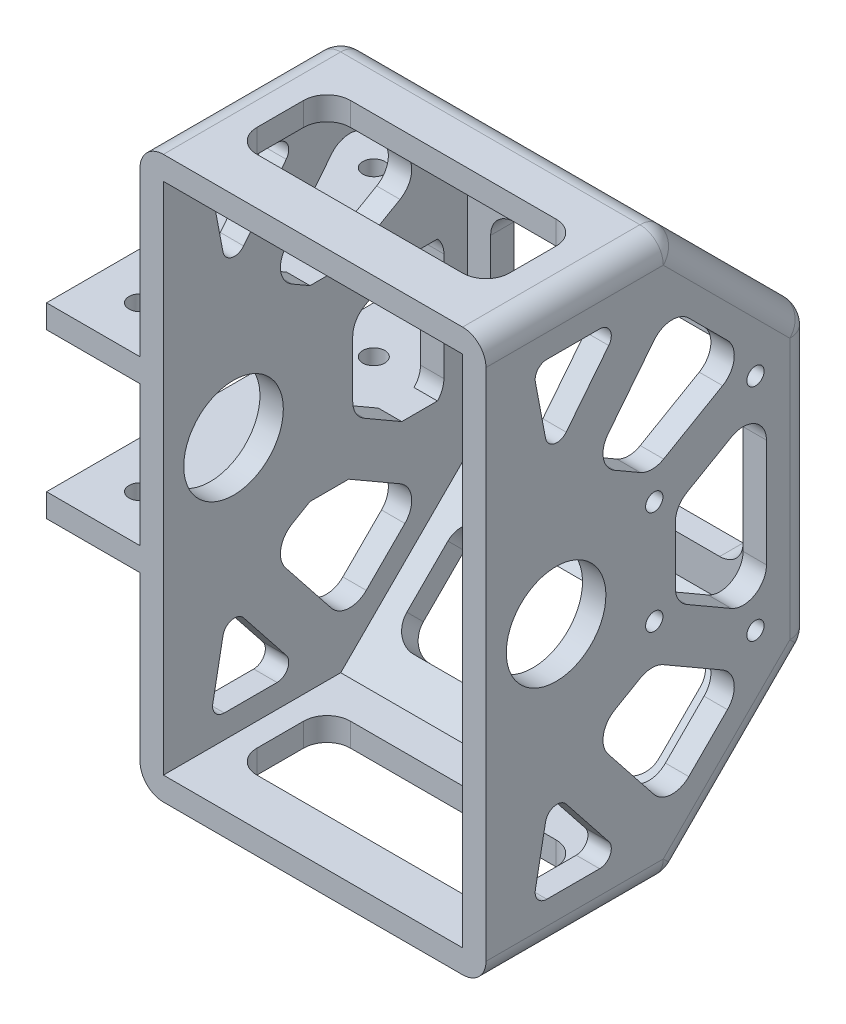
SolidWorks part; units mm, degrees
ref_plane "正面" through (0, 0, 0) normal (0, 0, 1) x (1, 0, 0)
ref_plane "平面" through (0, 0, 0) normal (0, 1, 0) x (1, 0, 0)
ref_plane "右側面" through (0, 0, 0) normal (1, 0, 0) x (0, 0, -1)
sketch "ｽｹｯﾁ1" plane through (0, 0, 0) normal (0, 0, 1) x (1, 0, 0)
  line L1 (-37, 60) -> (37, 60)
  line L2 (-37, 60) -> (-37, -60)
  line L3 (-37, -60) -> (37, -60)
  line L4 (37, 60) -> (37, -60)
  line L5 (-37, 60) -> (37, -60) construction
  line L6 (-37, -60) -> (37, 60) construction
  point P0 (0, 0)
  dimension "D1" = 120
  dimension "D2" = 74
extrude "ﾎﾞｽ - 押し出し1" add sketch "ｽｹｯﾁ1" along normal blind 70
chamfer "面取り2" distance 30 angle 45 2 edges at (0, 60, 0) (0, -60, 0)
sketch "ｽｹｯﾁ2" plane through (-37, 0, 0) normal (-1, 0, 0) x (0, 0, 1)
  line L0 (70, 60) -> (70, -60) construction
  line L1 (55, -23.6714) -> (55, -60)
  line L2 (55, 23.6714) -> (34.5, 11.8357)
  line L3 (34.5, 11.8357) -> (34.5, -11.8357)
  line L4 (34.5, -11.8357) -> (55, -23.6714)
  line L5 (55, -23.6714) -> (75.5, -11.8357)
  line L6 (75.5, -11.8357) -> (75.5, 11.8357)
  line L7 (75.5, 11.8357) -> (55, 23.6714)
  line L8 (70, -60) -> (30, -60) construction
  line L9 (34.5, -11.8357) -> (1.1122, -31.1122)
  line L10 (55, -23.6714) -> (34.1421, -50)
  line L11 (0, -30) -> (30, -60) construction
  line L12 (51.0808, -20.5665) -> (30.2229, -46.8952)
  line L14 (34.5, 11.8357) -> (1.1122, 31.1122)
  line L15 (30, 60) -> (0, 30) construction
  line L16 (32, -16.1658) -> (52.5, -28.0015)
  line L17 (32, -7.5056) -> (-1.3878, -26.782)
  line L18 (57.5, -28.0015) -> (80.5, -14.7224)
  line L19 (80.5, -14.7224) -> (80.5, 14.7224)
  line L20 (80.5, 14.7224) -> (57.5, 28.0015)
  line L21 (29.5, 11.8357) -> (29.5, -11.8357)
  line L22 (37, 16.1658) -> (3.6122, 35.4423)
  line L23 (52.5, 28.0015) -> (32, 16.1658)
  line L24 (55, 23.6714) -> (34.1421, 50)
  line L25 (58.9192, 26.7762) -> (38.0613, 53.1048)
  line L26 (37, -7.5056) -> (57.5, -19.3412)
  line L27 (37, -16.1658) -> (3.6122, -35.4423)
  line L28 (52.5, -19.3412) -> (70.5, -8.9489)
  line L29 (70.5, -8.9489) -> (70.5, 8.9489)
  line L30 (70.5, 8.9489) -> (52.5, 19.3412)
  line L31 (39.5, 11.8357) -> (39.5, -11.8357)
  line L32 (32, 7.5056) -> (-1.3878, 26.782)
  line L33 (57.5, 19.3412) -> (37, 7.5056)
  line L34 (58.9192, -26.7762) -> (38.0613, -53.1048)
  line L35 (51.0808, 20.5665) -> (30.2229, 46.8952)
  line L36 (55, 23.6714) -> (60, 50)
  line L37 (55, -23.6714) -> (60, -50)
  line L38 (50.0878, -24.6042) -> (55.0878, -50.9329)
  line L39 (59.9122, 22.7385) -> (64.9122, 49.0671)
  line L40 (59.9122, -22.7385) -> (64.9122, -49.0671)
  line L41 (50.0878, 24.6042) -> (55.0878, 50.9329)
  line L47 (60, 50) -> (34.1421, 50)
  line L48 (34.1421, 50) -> (10, 25.8579)
  line L49 (10, 25.8579) -> (10, -25.8579)
  line L50 (10, -25.8579) -> (34.1421, -50)
  line L51 (34.1421, -50) -> (60, -50)
  line L52 (60, -50) -> (60, 50)
  line L53 (60, 50) -> (34.1421, 50)
  line L54 (34.1421, 50) -> (10, 25.8579)
  line L55 (10, 25.8579) -> (10, -25.8579)
  line L56 (10, -25.8579) -> (34.1421, -50)
  line L57 (34.1421, -50) -> (60, -50)
  line L58 (60, -50) -> (60, 50)
  circle A0 centre (55, 0) radius 10.65
  circle A1 centre (55, 0) radius 20.5 construction
  dimension "D1" = 21.3
  dimension "D2" = 15
  dimension "D3" = 41
  dimension "D4" = 5
  dimension "D5" = 5
  dimension "D6" = 10
  dimension "D7" = 5
  dimension "D8" = 5
  dimension "D9" = 5
  dimension "D10" = 5
shell "ｼｪﾙ1" thickness 5
extrude "ｶｯﾄ - 押し出し1" cut sketch "ｽｹｯﾁ2" against normal through all
sketch "ｽｹｯﾁ3" plane through (0, -15, -15) normal (0, -0.7071, -0.7071) x (1, 0, 0)
  line L8 (-27, 53.6396) -> (-27, 31.2132)
  line L9 (-27, 31.2132) -> (27, 31.2132)
  line L10 (27, 31.2132) -> (27, 53.6396)
  line L11 (27, 53.6396) -> (-27, 53.6396)
  line L12 (-27, 53.6396) -> (-27, 31.2132)
  line L13 (-27, 31.2132) -> (27, 31.2132)
  line L14 (27, 31.2132) -> (27, 53.6396)
  line L15 (27, 53.6396) -> (-27, 53.6396)
  dimension "D1" = 10
extrude "ｶｯﾄ - 押し出し2" cut sketch "ｽｹｯﾁ3" against normal blind 70
sketch "ｽｹｯﾁ4" plane through (0, 15, -15) normal (0, 0.7071, -0.7071) x (1, 0, 0)
  line L8 (27, -53.6396) -> (27, -31.2132)
  line L9 (27, -31.2132) -> (-27, -31.2132)
  line L10 (-27, -31.2132) -> (-27, -53.6396)
  line L11 (-27, -53.6396) -> (27, -53.6396)
  line L12 (27, -53.6396) -> (27, -31.2132)
  line L13 (27, -31.2132) -> (-27, -31.2132)
  line L14 (-27, -31.2132) -> (-27, -53.6396)
  line L15 (-27, -53.6396) -> (27, -53.6396)
  dimension "D1" = 10
extrude "ｶｯﾄ - 押し出し3" cut sketch "ｽｹｯﾁ4" against normal blind 70
sketch "ｽｹｯﾁ5" plane through (0, 0, 0) normal (0, 0, -1) x (-1, 0, 0)
  line L8 (27, -20) -> (27, 20)
  line L9 (27, 20) -> (-27, 20)
  line L10 (-27, 20) -> (-27, -20)
  line L11 (-27, -20) -> (27, -20)
  line L12 (27, -20) -> (27, 20)
  line L13 (27, 20) -> (-27, 20)
  line L14 (-27, 20) -> (-27, -20)
  line L15 (-27, -20) -> (27, -20)
  dimension "D1" = 10
extrude "ｶｯﾄ - 押し出し4" cut sketch "ｽｹｯﾁ5" against normal blind 70
sketch "ｽｹｯﾁ7" plane through (0, 60, 0) normal (0, 1, 0) x (1, 0, 0)
  line L8 (27, -60) -> (27, -40)
  line L9 (27, -40) -> (-27, -40)
  line L10 (-27, -40) -> (-27, -60)
  line L11 (-27, -60) -> (27, -60)
  line L12 (27, -60) -> (27, -40)
  line L13 (27, -40) -> (-27, -40)
  line L14 (-27, -40) -> (-27, -60)
  line L15 (-27, -60) -> (27, -60)
  dimension "D1" = 10
extrude "ｶｯﾄ - 押し出し5" cut sketch "ｽｹｯﾁ7" against normal through all
fillet "ﾌｨﾚｯﾄ1" radius 5 58 edges at (27, 51.1612, 24.6967) (-27, 51.1612, 24.6967) (-27, 35.3033, 8.8388) (27, 35.3033, 8.8388) (-27, 20, 2.5) (-27, -20, 2.5) (27, 20, 2.5) (27, -20, 2.5) (-27, -35.3033, 8.8388) (-27, -51.1612, 24.6967) (27, -51.1612, 24.6967) (27, -35.3033, 8.8388) (34.5, -29.596, 13.7382) (34.5, -17.6092, 34.5) (34.5, 17.6092, 34.5) (34.5, 29.596, 13.7382) (34.5, -20.2073, 10) (34.5, -8.9489, 29.5) (34.5, 8.9489, 29.5) (34.5, 20.2073, 10) (-34.5, 29.596, 13.7382) (-34.5, 17.6092, 34.5) (-34.5, 20.2073, 10) (-34.5, 8.9489, 29.5) (-34.5, -20.2073, 10) (-34.5, -8.9489, 29.5) (-34.5, -29.596, 13.7382) (-34.5, -17.6092, 34.5) (-27, -57.5, 60) (-27, -57.5, 40) (27, -57.5, 40) (27, -57.5, 60) (27, 57.5, 60) (27, 57.5, 40) (-27, 57.5, 40) (-27, 57.5, 60) (37, -45, 15) (37, -60, 50) (-37, -60, 50) (-37, -45, 15) (0, -30, 0) (-37, 0, 0) (-37, 45, 15) (0, 60, 30) (-37, 60, 50) (37, 60, 50) (0, 30, 0) (37, 45, 15) (37, 0, 0) (0, -60, 30) (34.5, 46.4408, 30.5829) (34.5, 25.1059, 47.4847) (34.5, -46.4408, 30.5829) (34.5, -25.1059, 47.4847) (-34.5, 46.4408, 30.5829) (-34.5, 25.1059, 47.4847) (-34.5, -25.1059, 47.4847) (-34.5, -46.4408, 30.5829)
sketch "ｽｹｯﾁ10" plane through (-37, 0, 0) normal (-1, 0, 0) x (0, 0, 1)
  line L0 (5, 27.9289) -> (5, -27.9289) construction
  line L1 (70, 17.5) -> (5, 17.5)
  line L2 (70, 17.5) -> (70, -17.5)
  line L3 (70, -17.5) -> (5, -17.5)
  line L4 (5, 17.5) -> (5, -17.5)
  line L5 (70, 17.5) -> (5, -17.5) construction
  line L6 (70, -17.5) -> (5, 17.5) construction
  line L7 (70, 55) -> (70, -55) construction
  line L8 (70, -15) -> (5, -15)
  line L9 (70, 20) -> (5, 20)
  line L10 (70, -20) -> (5, -20)
  line L11 (70, 15) -> (5, 15)
  line L13 (5, -15) -> (0, -15)
  line L14 (5, -15) -> (5, -20)
  line L15 (5, -20) -> (0, -20)
  line L16 (0, -15) -> (0, -20)
  line L17 (2.5, -20) -> (2.5, -15) construction
  line L18 (5, -17.5) -> (0, -17.5) construction
  line L19 (5, 20) -> (0, 20)
  line L20 (5, 20) -> (5, 15)
  line L21 (5, 15) -> (0, 15)
  line L22 (0, 20) -> (0, 15)
  line L23 (2.5, 15) -> (2.5, 20) construction
  line L24 (5, 17.5) -> (0, 17.5) construction
  circle A0 centre (55, 0) radius 10.65 construction
  point P0 (37.5, 0)
  point P110 (2.5, -17.5)
  point P114 (2.5, 17.5)
  line M12 (42.4694, 22.2103) -> (37, 19.0526)
  arc M13 (37, 19.0526) -> (32, 19.0526) centre (34.5, 23.3827) cw
  line M14 (32, 19.0526) -> (19.3813, 26.338)
  arc M17 (10, 11.547) -> (17.5, 15.8771) centre (15, 11.547) cw
  line M18 (17.5, 15.8771) -> (27, 10.3923)
  line M22 (27, -10.3923) -> (17.5, -15.8771)
  arc M23 (17.5, -15.8771) -> (10, -11.547) centre (15, -11.547) cw
  line M28 (19.3813, -26.338) -> (32, -19.0526)
  arc M29 (32, -19.0526) -> (37, -19.0526) centre (34.5, -23.3827) cw
  line M30 (37, -19.0526) -> (42.4694, -22.2103)
  line M36 (70, -55) -> (70, 55)
  line M39 (5, 27.9289) -> (5, -27.9289)
  dimension "D1" = 0
  dimension "D2" = 35
  dimension "D3" = 0
  dimension "D4" = 2.5
  dimension "D5" = 2.5
extrude "ﾎﾞｽ - 押し出し3" add sketch "ｽｹｯﾁ10" along normal blind 20 and the other way blind 5 contours L8 L4 L3 M36 M22 M23 | L10 L3 M36 M39 M28 M29 M30 | L11 L1 M36 M39 M17 M18 | L9 L1 M36 M12 M13 M14 M39 | L10 M30 M29 M28 | L9 M12 M14 M13 | L8 M22 M23 | L11 M18 M17 | L19 L22 L21 M39 | L13 L16 L15 L4 M39
sketch "ｽｹｯﾁ12" plane through (0, -20, 0) normal (0, -1, 0) x (1, 0, 0)
  line L0 (-57, 70) -> (-57, 0) construction
  line L1 (-37, 70) -> (-57, 70) construction
  line L2 (-57, 70) -> (-57, 0) construction
  circle A0 centre (-47, 60) radius 2.35
  circle A1 centre (-47, 10) radius 2.35
  dimension "D1" = 10
  dimension "D2" = 10
  dimension "D3" = 4.7
  dimension "D4" = 50
  dimension "D5" = 4.7
  dimension "D6" = 10
extrude "ｶｯﾄ - 押し出し7" cut sketch "ｽｹｯﾁ12" against normal through all
sketch "ｽｹｯﾁ13" plane through (37, 0, 0) normal (1, 0, 0) x (0, 0, -1)
  line L0 (-34, -10.0111) -> (-12.3494, -22.5111) construction
  line L1 (-34, -10.0111) -> (-34, 12.1244) construction
  line L2 (-34, 12.1244) -> (-12.3494, 24.6244) construction
  line L3 (-12.3494, 24.6244) -> (-12.3494, -22.5111) construction
  circle A0 centre (-12.3494, 24.6244) radius 1.85
  circle A1 centre (-34, 12.1244) radius 1.85
  circle A2 centre (-34, -10.0111) radius 1.85
  circle A3 centre (-12.3494, -22.5111) radius 1.85
  dimension "D1" = 3.7
  dimension "D2" = 3.7
  dimension "D3" = 3.7
  dimension "D4" = 3.7
extrude "ｶｯﾄ - 押し出し8" cut sketch "ｽｹｯﾁ13" against normal blind 10
fillet "ﾌｨﾚｯﾄ2" radius 2.5 12 edges at (-34.5, -30.1664, 56.2334) (-34.5, -50, 40.521) (-34.5, -50, 60) (-34.5, 30.1664, 56.2334) (-34.5, 50, 60) (-34.5, 50, 40.521) (34.5, -50, 40.521) (34.5, -50, 60) (34.5, -30.1664, 56.2334) (34.5, 30.1664, 56.2334) (34.5, 50, 60) (34.5, 50, 40.521)
